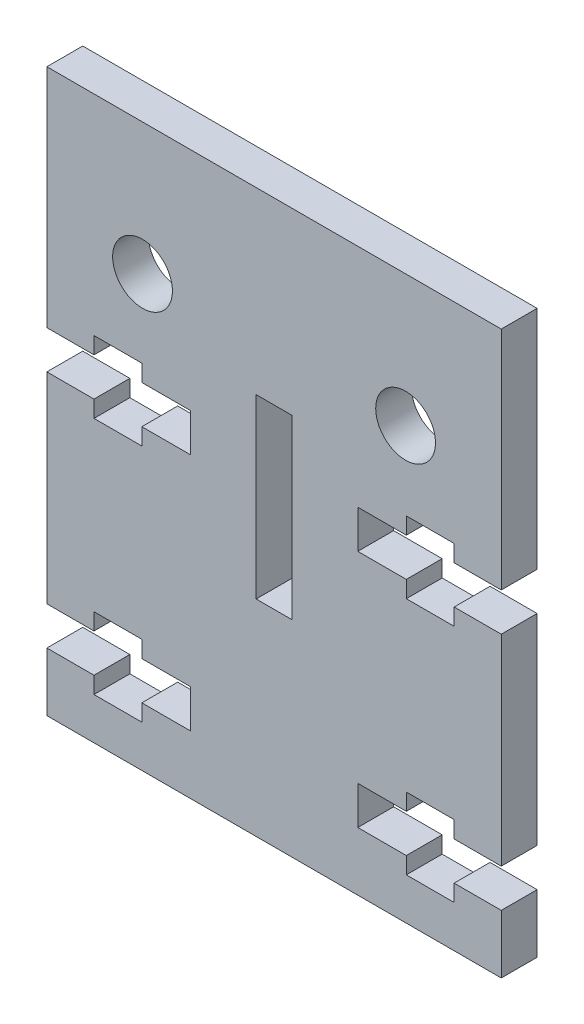
SolidWorks part; units mm, degrees
ref_plane "Plan de face" through (0, 0, 0) normal (0, 0, 1) x (1, 0, 0)
ref_plane "Plan de dessus" through (0, 0, 0) normal (0, 1, 0) x (1, 0, 0)
ref_plane "Plan de droite" through (0, 0, 0) normal (1, 0, 0) x (0, 0, -1)
sketch "Sketch1" plane through (0, 0, 0) normal (0, 0, 1) x (1, 0, 0)
  line L1 (-19, 16.6049) -> (19, 16.6049)
  line L2 (-19, 16.6049) -> (-19, -30.3951)
  line L3 (-19, -30.3951) -> (19, -30.3951)
  line L4 (19, 16.6049) -> (19, -30.3951)
  point P4 (0, 16.6049)
  dimension "D1" = 38
  dimension "D2" = 47
extrude "Boss-Extrude1" add sketch "Sketch1" along normal blind 3
sketch "Sketch2" plane through (0, 0, 3) normal (0, 0, 1) x (1, 0, 0)
  line L0 (0, 16.6049) -> (0, -30.3951) construction
  line L1 (19, 16.6049) -> (-19, 16.6049) construction
  line L2 (-19, -30.3951) -> (19, -30.3951) construction
  circle A0 centre (-11, 5.6049) radius 2.5
  circle A1 centre (11, 5.6049) radius 2.5
  dimension "D1" = 11
  dimension "D2" = 11
extrude "Cut-Extrude1" cut sketch "Sketch2" against normal blind 3
sketch "Sketch3" plane through (0, 0, 3) normal (0, 0, 1) x (1, 0, 0)
  line L0 (-13.9059, -3.3951) -> (-13.8091, -3.3951) construction
  line L1 (19, 16.6049) -> (-19, 16.6049) construction
  line L2 (-13.9059, -23.3951) -> (12.4268, -23.3951) construction
  line L3 (-19, 16.6049) -> (-19, -30.3951) construction
  line L4 (-7, -5.4951) -> (-11.0591, -5.4951)
  line L5 (-7, -5.4951) -> (-7, -2.2951)
  line L6 (-7, -2.2951) -> (-11.0591, -2.2951)
  line L7 (-19, -5.4951) -> (-19, -2.2951)
  line L8 (-15.0591, -2.2951) -> (-19, -2.2951)
  line L9 (7, -5.4951) -> (11.0591, -5.4951)
  line L10 (0, 16.6049) -> (0, -30.3951) construction
  line L11 (-15.0591, -0.8951) -> (-11.0591, -0.8951)
  line L12 (-15.0591, -0.8951) -> (-15.0591, -2.2951)
  line L13 (-15.0591, -6.8951) -> (-11.0591, -6.8951)
  line L14 (-11.0591, -0.8951) -> (-11.0591, -2.2951)
  line L15 (11.0591, -5.4951) -> (11.0591, -6.8951)
  line L16 (15.0591, -6.8951) -> (11.0591, -6.8951)
  line L17 (-19, -30.3951) -> (19, -30.3951) construction
  line L18 (-7, -3.3951) -> (12.4268, -3.3951) construction
  line L19 (-11.0591, -5.4951) -> (-11.0591, -6.8951)
  line L22 (-15.0591, -5.4951) -> (-19, -5.4951)
  line L23 (-15.0591, -5.4951) -> (-15.0591, -6.8951)
  line L24 (15.0591, -5.4951) -> (15.0591, -6.8951)
  line L25 (15.0591, -5.4951) -> (19, -5.4951)
  line L26 (19, -5.4951) -> (19, -2.2951)
  line L27 (15.0591, -2.2951) -> (19, -2.2951)
  line L28 (15.0591, -0.8951) -> (15.0591, -2.2951)
  line L29 (15.0591, -0.8951) -> (11.0591, -0.8951)
  line L30 (11.0591, -0.8951) -> (11.0591, -2.2951)
  line L31 (7, -2.2951) -> (11.0591, -2.2951)
  line L32 (7, -5.4951) -> (7, -2.2951)
  line L33 (-7, -25.4951) -> (-7, -22.2951)
  line L34 (-7, -22.2951) -> (-11.0591, -22.2951)
  line L35 (-11.0591, -20.8951) -> (-11.0591, -22.2951)
  line L36 (-15.0591, -20.8951) -> (-11.0591, -20.8951)
  line L37 (-15.0591, -20.8951) -> (-15.0591, -22.2951)
  line L38 (-15.0591, -22.2951) -> (-19, -22.2951)
  line L39 (-19, -25.4951) -> (-19, -22.2951)
  line L40 (-15.0591, -25.4951) -> (-19, -25.4951)
  line L41 (-15.0591, -25.4951) -> (-15.0591, -26.8951)
  line L42 (-15.0591, -26.8951) -> (-11.0591, -26.8951)
  line L43 (-11.0591, -25.4951) -> (-11.0591, -26.8951)
  line L44 (-7, -25.4951) -> (-11.0591, -25.4951)
  line L45 (7, -25.4951) -> (11.0591, -25.4951)
  line L46 (11.0591, -25.4951) -> (11.0591, -26.8951)
  line L47 (15.0591, -26.8951) -> (11.0591, -26.8951)
  line L48 (15.0591, -25.4951) -> (15.0591, -26.8951)
  line L49 (15.0591, -25.4951) -> (19, -25.4951)
  line L50 (19, -25.4951) -> (19, -22.2951)
  line L51 (15.0591, -22.2951) -> (19, -22.2951)
  line L52 (15.0591, -20.8951) -> (15.0591, -22.2951)
  line L53 (15.0591, -20.8951) -> (11.0591, -20.8951)
  line L54 (11.0591, -20.8951) -> (11.0591, -22.2951)
  line L55 (7, -22.2951) -> (11.0591, -22.2951)
  line L56 (7, -25.4951) -> (7, -22.2951)
  point P6 (-13.8091, -3.3951)
  point P13 (-13.8091, -3.3951)
  dimension "D1" = 20
  dimension "D2" = 26.3327
  dimension "D3" = 20
  dimension "D4" = 12
  dimension "D5" = 3.2
  dimension "D6" = 4
  dimension "D7" = 6
  dimension "D8" = 2
extrude "Cut-Extrude2" cut sketch "Sketch3" against normal blind 3
sketch "Sketch4" plane through (0, 0, 3) normal (0, 0, 1) x (1, 0, 0)
  line L1 (-1.5, 1.6049) -> (1.5, 1.6049)
  line L2 (-1.5, 1.6049) -> (-1.5, -13.1951)
  line L3 (-1.5, -13.1951) -> (1.5, -13.1951)
  line L4 (1.5, 1.6049) -> (1.5, -13.1951)
  point P4 (0, 1.6049)
  dimension "D1" = 3
  dimension "D2" = 2.5
  dimension "D3" = 14.8
extrude "Cut-Extrude3" cut sketch "Sketch4" against normal blind 10
